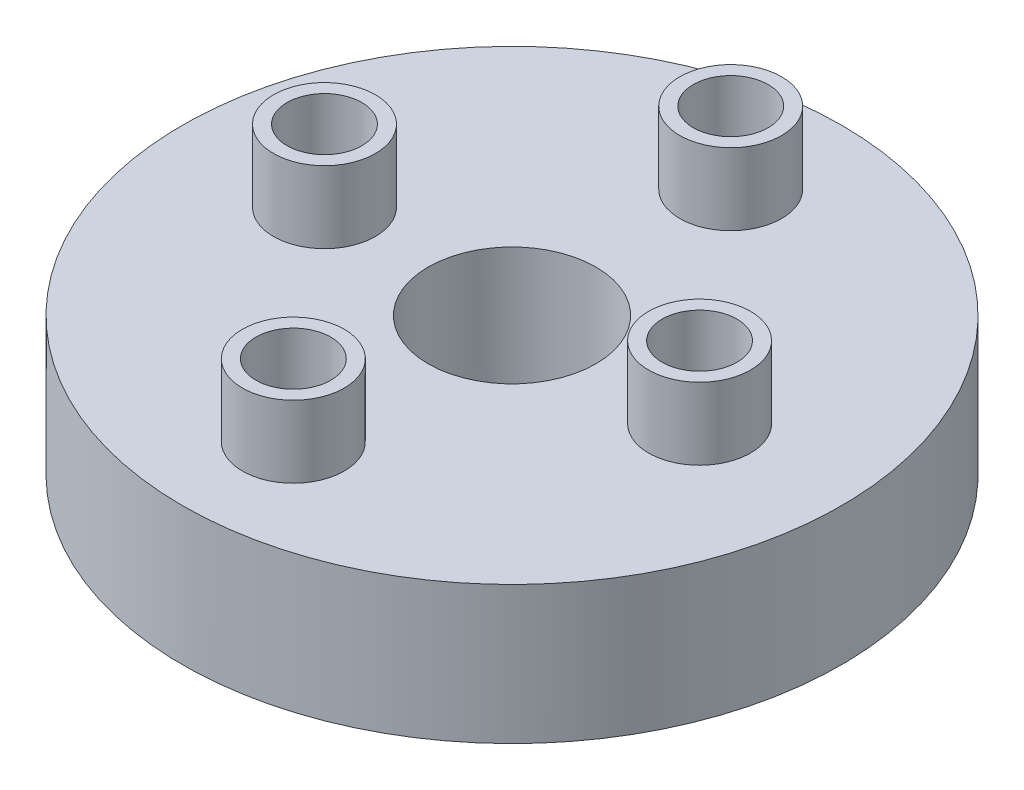
SolidWorks part; units mm, degrees
ref_plane "Front Plane" through (0, 0, 0) normal (0, 0, 1) x (1, 0, 0)
ref_plane "Top Plane" through (0, 0, 0) normal (0, 1, 0) x (1, 0, 0)
ref_plane "Right Plane" through (0, 0, 0) normal (1, 0, 0) x (0, 0, -1)
sketch "Sketch1" plane through (0, 0, 0) normal (0, 1, 0) x (1, 0, 0)
  line L0 (0, 13.97) -> (0, -13.97) construction
  line L1 (-13.97, 0) -> (13.97, 0) construction
  line L2 (0, 0) -> (0, 9.271)
  line L3 (0, 0) -> (7.9502, 0)
  circle A0 centre (0, 0) radius 13.97
  circle A1 centre (0, 9.271) radius 2.159
  circle A2 centre (0, -9.271) radius 2.159
  circle A3 centre (7.9502, 0) radius 2.159
  circle A4 centre (-7.9502, 0) radius 2.159
  circle A5 centre (0, 0) radius 3.556
  circle A6 centre (-7.9502, 0) radius 1.5875
  circle A7 centre (7.9502, 0) radius 1.5875
  circle A8 centre (0, 9.271) radius 1.5875
  circle A9 centre (0, -9.271) radius 1.5875
  circle A10 centre (-7.9502, 0) radius 2.159
  circle A11 centre (0, -9.271) radius 2.159
  circle A12 centre (7.9502, 0) radius 2.159
  circle A13 centre (0, 9.271) radius 2.159
  dimension "D1" = 27.94
  dimension "D3" = 4.318
  dimension "D5" = 4.318
  dimension "D6" = 7.112
  dimension "D7" = 3.175
  dimension "D8" = 3.175
  dimension "D2" = 9.271
  dimension "D4" = 7.9502
extrude "Boss-Extrude4" add sketch "Sketch1" along normal blind 2.54
ref_plane "Plane2" through (0, 2.54, 0) normal (0, 1, 0) x (1, 0, 0)
sketch "Sketch2" plane through (0, 2.54, 0) normal (0, 1, 0) x (1, 0, 0)
  line L0 (0, 0) -> (0, 9.271) construction
  line L1 (0, 0) -> (7.9502, 0) construction
  line L2 (0, 0) -> (0, 9.271)
  line L3 (0, 0) -> (7.9502, 0)
  circle A0 centre (-7.9502, 0) radius 2.159
  circle A1 centre (0, 0) radius 3.556
  circle A2 centre (0, 0) radius 3.556
  circle A3 centre (-7.9502, 0) radius 2.159
  circle A4 centre (-7.9502, 0) radius 2.159
  circle A5 centre (7.9502, 0) radius 2.159
  circle A6 centre (7.9502, 0) radius 2.159
  circle A7 centre (0, -9.271) radius 2.159
  circle A8 centre (0, -9.271) radius 2.159
  circle A9 centre (0, 9.271) radius 2.159
  circle A10 centre (0, 9.271) radius 2.159
  circle A11 centre (0, 0) radius 13.97
  circle A12 centre (0, 0) radius 13.97
  circle A13 centre (0, 9.271) radius 2.159
  circle A14 centre (0, 9.271) radius 2.159
  circle A15 centre (7.9502, 0) radius 2.159
  circle A16 centre (7.9502, 0) radius 2.159
  circle A17 centre (0, -9.271) radius 2.159
  circle A18 centre (0, -9.271) radius 2.159
  circle A19 centre (-7.9502, 0) radius 2.159
  circle A20 centre (-7.9502, 0) radius 2.159
  circle A21 centre (0, -9.271) radius 1.5875
  circle A22 centre (0, -9.271) radius 1.5875
  circle A23 centre (0, 9.271) radius 1.5875
  circle A24 centre (0, 9.271) radius 1.5875
  circle A25 centre (7.9502, 0) radius 1.5875
  circle A26 centre (7.9502, 0) radius 1.5875
  circle A27 centre (-7.9502, 0) radius 1.5875
  circle A28 centre (-7.9502, 0) radius 1.5875
  circle A29 centre (0, 9.271) radius 2.159
  circle A30 centre (7.9502, 0) radius 2.159
  circle A31 centre (0, -9.271) radius 2.159
  dimension "D1" = 0
  dimension "D2" = 0
  dimension "D3" = 0
  dimension "D4" = 0
  dimension "D5" = 0
  dimension "D6" = 0
  dimension "D7" = 0
  dimension "D8" = 0
  dimension "D9" = 0
  dimension "D10" = 0
  dimension "D11" = 0
  dimension "D12" = 0
  dimension "D13" = 0
  dimension "D14" = 0
extrude "Boss-Extrude6" add sketch "Sketch2" along normal blind 3.048
ref_plane "Plane3" through (0, 0, 0) normal (0, -1, 0) x (-1, 0, 0)
sketch "Sketch3" plane through (0, 0, 0) normal (0, -1, 0) x (-1, 0, 0)
  line L0 (0, 0) -> (0, 9.271) construction
  line L1 (0, 0) -> (-7.9502, 0) construction
  line L2 (0, 0) -> (0, 9.271)
  line L3 (0, 0) -> (-7.9502, 0)
  circle A0 centre (0, 9.271) radius 2.921
  circle A1 centre (0, 0) radius 3.556
  circle A2 centre (0, 0) radius 3.556
  circle A3 centre (7.9502, 0) radius 2.159
  circle A4 centre (7.9502, 0) radius 2.159
  circle A5 centre (-7.9502, 0) radius 2.159
  circle A6 centre (-7.9502, 0) radius 2.159
  circle A7 centre (0, -9.271) radius 2.159
  circle A8 centre (0, -9.271) radius 2.159
  circle A9 centre (0, 9.271) radius 2.159
  circle A10 centre (0, 9.271) radius 2.159
  circle A11 centre (0, 0) radius 13.97
  circle A12 centre (0, 0) radius 13.97
  circle A13 centre (0, 9.271) radius 2.159
  circle A14 centre (0, 9.271) radius 2.159
  circle A15 centre (-7.9502, 0) radius 2.159
  circle A16 centre (-7.9502, 0) radius 2.159
  circle A17 centre (0, -9.271) radius 2.159
  circle A18 centre (0, -9.271) radius 2.159
  circle A19 centre (7.9502, 0) radius 2.159
  circle A20 centre (7.9502, 0) radius 2.159
  circle A21 centre (0, -9.271) radius 1.5875
  circle A22 centre (0, -9.271) radius 1.5875
  circle A23 centre (0, 9.271) radius 1.5875
  circle A24 centre (0, 9.271) radius 1.5875
  circle A25 centre (-7.9502, 0) radius 1.5875
  circle A26 centre (-7.9502, 0) radius 1.5875
  circle A27 centre (7.9502, 0) radius 1.5875
  circle A28 centre (7.9502, 0) radius 1.5875
  circle A29 centre (0, -9.271) radius 2.921
  circle A30 centre (-7.9502, 0) radius 2.921
  circle A31 centre (7.9502, 0) radius 2.921
  dimension "D15" = 4.318
  dimension "D16" = 5.842
  dimension "D17" = 5.842
  dimension "D1" = 0
  dimension "D2" = 0
  dimension "D3" = 0
  dimension "D4" = 0
  dimension "D5" = 0
  dimension "D6" = 0
  dimension "D7" = 0
  dimension "D8" = 0
  dimension "D9" = 0
  dimension "D10" = 0
  dimension "D11" = 0
  dimension "D12" = 0
  dimension "D13" = 0
  dimension "D14" = 0
extrude "Boss-Extrude7" add sketch "Sketch3" along normal blind 3.302
